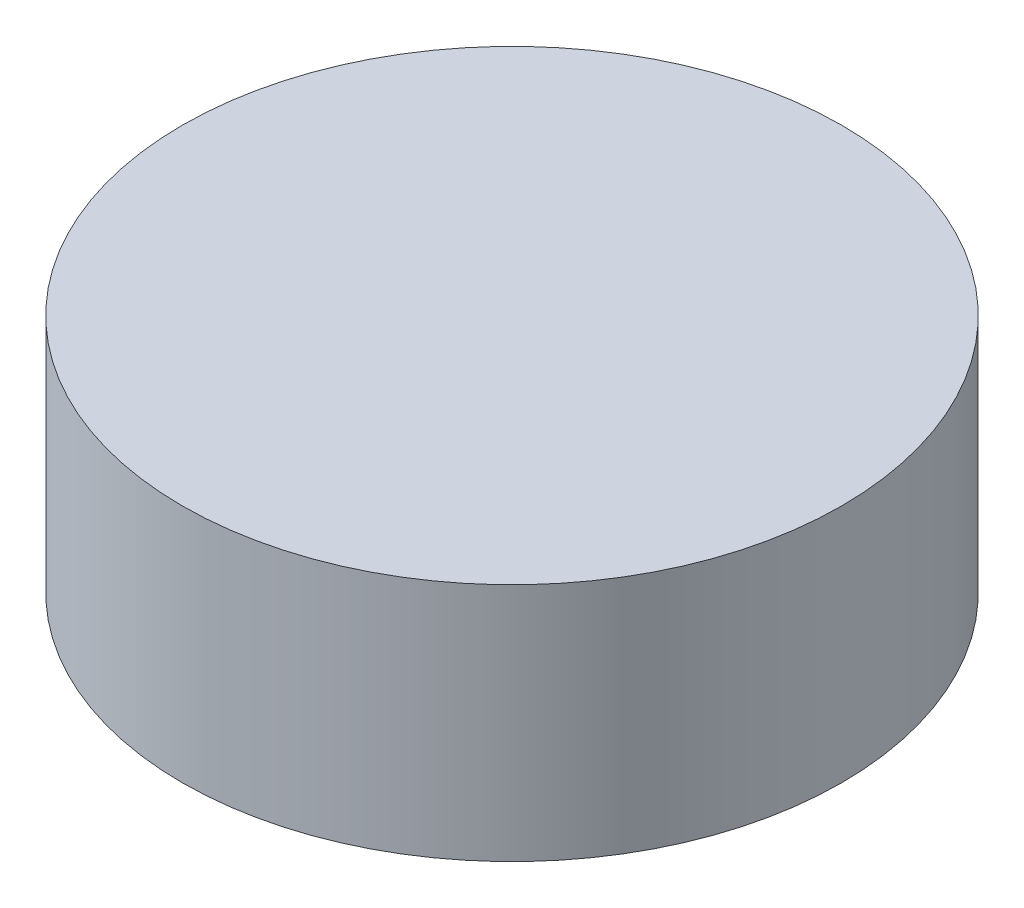
SolidWorks part; units mm, degrees
ref_plane "Front Plane" through (0, 0, 0) normal (0, 0, 1) x (1, 0, 0)
ref_plane "Top Plane" through (0, 0, 0) normal (0, 1, 0) x (1, 0, 0)
ref_plane "Right Plane" through (0, 0, 0) normal (1, 0, 0) x (0, 0, -1)
sketch "Sketch1" plane through (0, 0, 0) normal (0, 0, 1) x (1, 0, 0)
  line L7 (0, 0) -> (25.4, 0)
  line L8 (25.4, 0) -> (25.4, -17.78)
  line L9 (0, 2.54) -> (27.94, 2.54)
  line L10 (27.94, 2.54) -> (27.94, -17.78)
  line L11 (0, 0) -> (0, 2.54)
  line L12 (25.4, -17.78) -> (27.94, -17.78)
  point P0 (26.67, -17.78)
  dimension "D2" = 27.94
  dimension "D1" = 20.32
  dimension "D3" = 2.54
revolve "Revolve1" add sketch "Sketch1" angle 360 about L11
